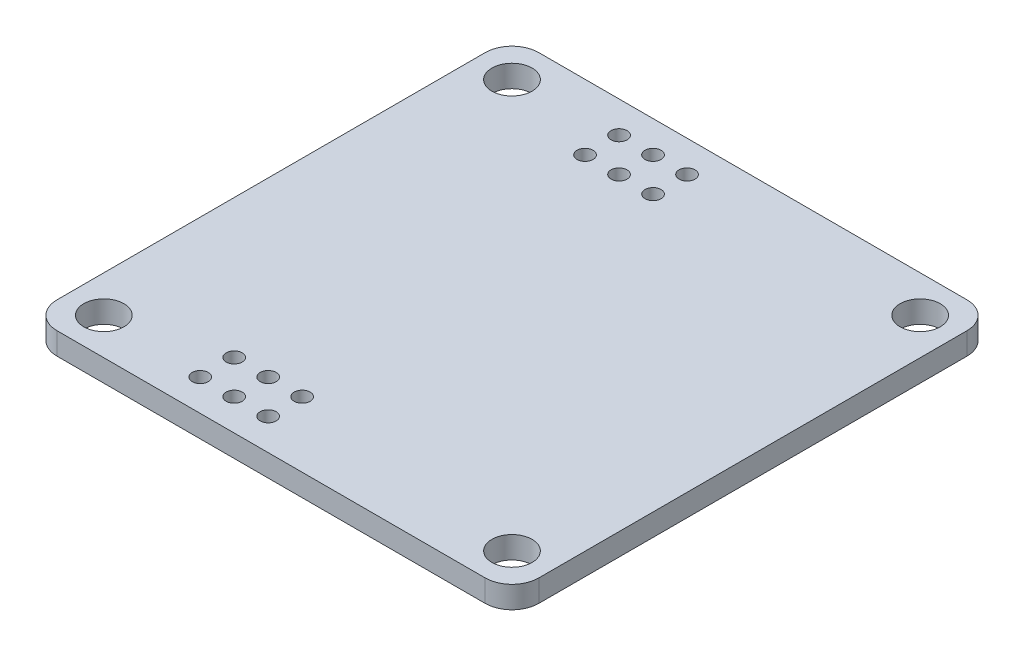
SolidWorks part; units mm, degrees
ref_plane "Front Plane" through (0, 0, 0) normal (0, 0, 1) x (1, 0, 0)
ref_plane "Top Plane" through (0, 0, 0) normal (0, 1, 0) x (1, 0, 0)
ref_plane "Right Plane" through (0, 0, 0) normal (1, 0, 0) x (0, 0, -1)
sketch "Sketch1" plane through (0, 0, 0) normal (0, 1, 0) x (1, 0, 0)
  line L0 (0, 18) -> (0, -18) construction
  line L1 (-18, 18) -> (18, 18)
  line L2 (-18, 18) -> (-18, -18)
  line L3 (-18, -18) -> (18, -18)
  line L4 (18, 18) -> (18, -18)
  line L5 (-18, 18) -> (18, -18) construction
  line L6 (-18, -18) -> (18, 18) construction
  line L7 (-18, 0) -> (18, 0) construction
  circle A0 centre (-15.25, 15.25) radius 1.5
  circle A1 centre (15.25, 15.25) radius 1.5
  circle A2 centre (15.25, -15.25) radius 1.5
  circle A3 centre (-15.25, -15.25) radius 1.5
  point P0 (0, 0)
  dimension "D2" = 3
  dimension "D1" = 36
  dimension "D3" = 30.5
extrude "Base shape" add sketch "Sketch1" along normal blind 1.65
fillet "Rounded corners" radius 2 4 edges at (-18, 0.825, -18) (18, 0.825, -18) (18, 0.825, 18) (-18, 0.825, 18)
sketch "Sketch2" plane through (0, 1.65, 0) normal (0, 1, 0) x (1, 0, 0)
  line L0 (-7.65, 18) -> (-7.65, -18) construction
  line L1 (16, 18) -> (-16, 18) construction
  line L2 (-16, -18) -> (16, -18) construction
  line L3 (-18, 16) -> (-18, -16) construction
  line L4 (-18, 15.65) -> (18, 15.65) construction
  line L5 (18, -16) -> (18, 16) construction
  line L6 (-18, 0) -> (18, 0) construction
  line L7 (-7.65, 15.65) -> (-5.11, 15.65) construction
  line L8 (-2.57, 15.65) -> (-2.57, 13.11) construction
  circle A0 centre (-5.11, 15.65) radius 0.6
  circle A1 centre (-7.65, 15.65) radius 0.6
  circle A2 centre (-2.57, 15.65) radius 0.6
  circle A3 centre (-5.11, 13.11) radius 0.6
  circle A4 centre (-2.57, 13.11) radius 0.6
  circle A5 centre (-7.65, 13.11) radius 0.6
  circle A6 centre (-2.57, -13.11) radius 0.6
  circle A7 centre (-2.57, -15.65) radius 0.6
  circle A8 centre (-5.11, -13.11) radius 0.6
  circle A9 centre (-5.11, -15.65) radius 0.6
  circle A10 centre (-7.65, -13.11) radius 0.6
  circle A11 centre (-7.65, -15.65) radius 0.6
  dimension "D1" = 1.2
  dimension "D2" = 10.35
  dimension "D3" = 2.35
  dimension "D6" = 2.54
  dimension "D4" = 3
  dimension "D5" = 2
extrude "Pinheader holes" cut sketch "Sketch2" against normal up to next
